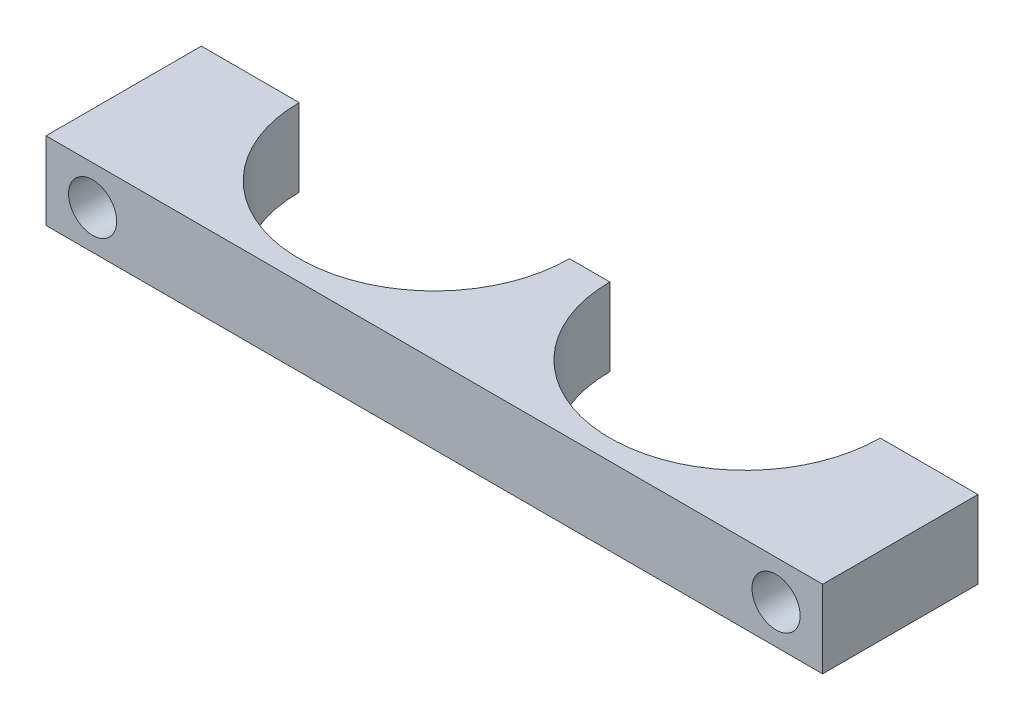
SolidWorks part; units mm, degrees
ref_plane "Front Plane" through (0, 0, 0) normal (0, 0, 1) x (1, 0, 0)
ref_plane "Top Plane" through (0, 0, 0) normal (0, 1, 0) x (1, 0, 0)
ref_plane "Right Plane" through (0, 0, 0) normal (1, 0, 0) x (0, 0, -1)
sketch "Sketch1" plane through (0, 0, 0) normal (0, 1, 0) x (1, 0, 0)
  line L0 (12.7928, -1.7622) -> (17.9928, -1.7622)
  line L1 (-34.6072, -1.7622) -> (-22.0072, -1.7622)
  line L2 (-34.6072, -1.7622) -> (-34.6072, -21.7622)
  line L3 (-34.6072, -21.7622) -> (65.3928, -21.7622)
  line L4 (65.3928, -1.7622) -> (65.3928, -21.7622)
  line L5 (52.7928, -1.7622) -> (65.3928, -1.7622)
  arc A0 (-22.0072, -1.7622) -> (12.7928, -1.7622) centre (-4.6072, -1.7622) ccw
  arc A1 (17.9928, -1.7622) -> (52.7928, -1.7622) centre (35.3928, -1.7622) ccw
  dimension "D3" = 34.8
  dimension "D4" = 34.8
  dimension "D1" = 100
  dimension "D2" = 40
  dimension "D6" = 20
extrude "Boss-Extrude1" add sketch "Sketch1" along normal blind 10
sketch "Sketch2" plane through (0, 0, 21.7622) normal (0, 0, 1) x (1, 0, 0)
  line L0 (-34.6072, 10) -> (-34.6072, 0) construction
  line L1 (65.3928, 10) -> (65.3928, 0) construction
  line L2 (-34.6072, 0) -> (65.3928, 0) construction
  circle A0 centre (-28.6072, 5) radius 3.1
  circle A1 centre (59.3928, 5) radius 3.1
  dimension "D4" = 6.2
  dimension "D5" = 6.2
  dimension "D1" = 6
  dimension "D2" = 6
  dimension "D3" = 5
  dimension "D6" = 5
extrude "Cut-Extrude1" cut sketch "Sketch2" against normal through all
